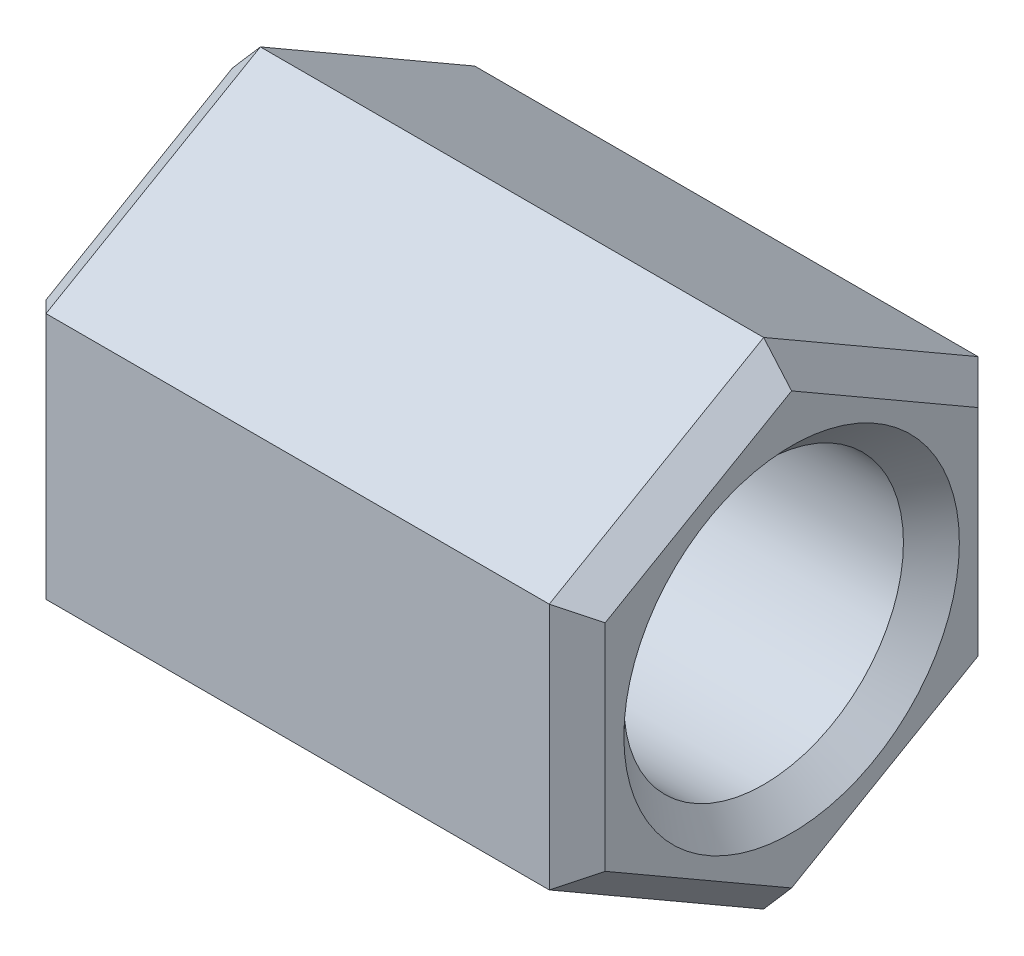
SolidWorks part; units mm, degrees
material "黄铜"
ref_plane "前视基准面" through (0, 0, 0) normal (1, 0, 0) x (0, 1, 0)
ref_plane "上视基准面" through (0, 0, 0) normal (0, 0, 1) x (0, 1, 0)
ref_plane "右视基准面" through (0, 0, 0) normal (0, 1, 0) x (-1, 0, 0)
other "Configuration Table"
sketch "草图1" plane through (0, 0, 0) normal (1, 0, 0) x (0, 1, 0)
  line L0 (0, 0) -> (2.6558, 0) construction
  line L1 (2.6558, 0) -> (1.3279, 2.3)
  line L2 (1.3279, 2.3) -> (-1.3279, 2.3)
  line L3 (-1.3279, 2.3) -> (-2.6558, 0)
  line L4 (-2.6558, 0) -> (-1.3279, -2.3)
  line L5 (-1.3279, -2.3) -> (1.3279, -2.3)
  line L6 (1.3279, -2.3) -> (2.6558, 0)
  circle A0 centre (0, 0) radius 1.5
  circle A1 centre (0, 0) radius 2.3 construction
  dimension "D1" = 3
  dimension "D2" = 4.6
extrude "凸台-拉伸1" add sketch "草图1" along normal blind 6
chamfer "倒角1" distance 0.3 angle 45 14 edges at (0, 0, -1.5) (0, 1.9919, 1.15) (0, 0, 2.3) (0, -1.9919, 1.15) (0, -1.9919, -1.15) (0, 0, -2.3) (0, 1.9919, -1.15) (6, 0, -1.5) (6, 0, -2.3) (6, -1.9919, -1.15) (6, -1.9919, 1.15) (6, 0, 2.3) (6, 1.9919, 1.15) (6, 1.9919, -1.15)
